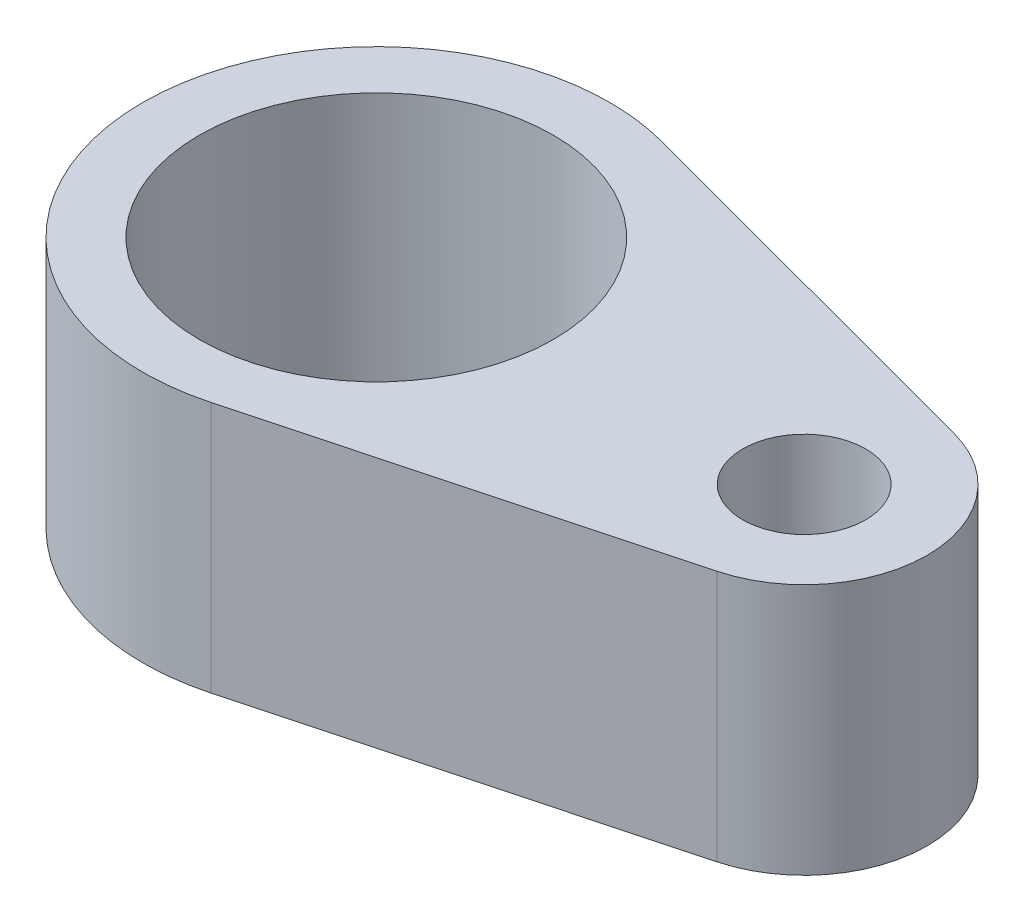
SolidWorks part; units mm, degrees
material "ABS"
ref_plane "Front Plane" through (0, 0, 0) normal (0, 0, 1) x (1, 0, 0)
ref_plane "Top Plane" through (0, 0, 0) normal (0, 1, 0) x (1, 0, 0)
ref_plane "Right Plane" through (0, 0, 0) normal (1, 0, 0) x (0, 0, -1)
sketch "Sketch2" plane through (0, 0, 0) normal (0, 1, 0) x (1, 0, 0)
  line L0 (3.1203, 11.6545) -> (23.7402, 6.134)
  line L1 (3.1203, -11.6545) -> (23.7402, -6.134)
  circle A0 centre (0, 0) radius 9.144
  circle A1 centre (22.098, 0) radius 3.175
  circle A2 centre (0, 0) radius 12.065 construction
  circle A3 centre (22.098, 0) radius 6.35 construction
  arc A4 (3.1203, 11.6545) -> (3.1203, -11.6545) centre (0, 0) ccw
  arc A5 (23.7402, 6.134) -> (23.7402, -6.134) centre (22.098, 0) cw
  dimension "D1" = 18.288
  dimension "D2" = 6.35
  dimension "D4" = 24.13
  dimension "D5" = 12.7
  dimension "D3" = 22.098
extrude "Boss-Extrude1" add sketch "Sketch2" along normal blind 13
